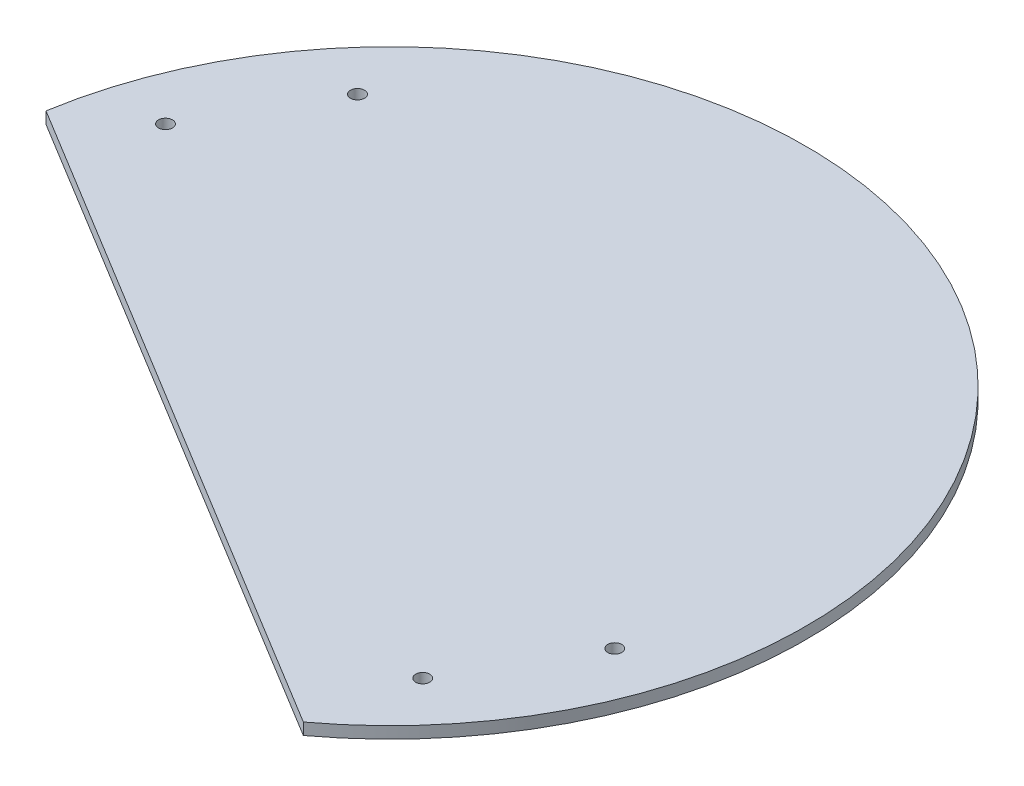
SolidWorks part; units mm, degrees
ref_plane "前视基准面" through (0, 0, 0) normal (0, 0, 1) x (1, 0, 0)
ref_plane "上视基准面" through (0, 0, 0) normal (0, 1, 0) x (1, 0, 0)
ref_plane "右视基准面" through (0, 0, 0) normal (1, 0, 0) x (0, 0, -1)
other "Configuration Table"
sketch "草图1" plane through (0, 0, 0) normal (0, 1, 0) x (1, 0, 0)
  line L0 (-39.8854, -89.0517) -> (240.9608, -260.0375)
  circle A1 centre (20.4352, -16.4023) radius 3 construction
  circle A2 centre (20.4352, -16.4023) radius 3
  circle A3 centre (-9.5648, -68.3639) radius 3 construction
  circle A4 centre (-9.5648, -68.3639) radius 3
  circle A5 centre (250.2428, -218.3639) radius 3 construction
  circle A6 centre (250.2428, -218.3639) radius 3
  circle A7 centre (135.339, -117.3831) radius 152.9706 construction
  circle A8 centre (280.2428, -166.4023) radius 3
  circle A9 centre (280.2428, -166.4023) radius 3
  arc A10 (240.9608, -260.0375) -> (-39.8854, -89.0517) centre (135.339, -117.3831) ccw
  dimension "D2" = 355
  dimension "D1" = 0
extrude "凸台-拉伸1" add sketch "草图1" along normal blind 5
